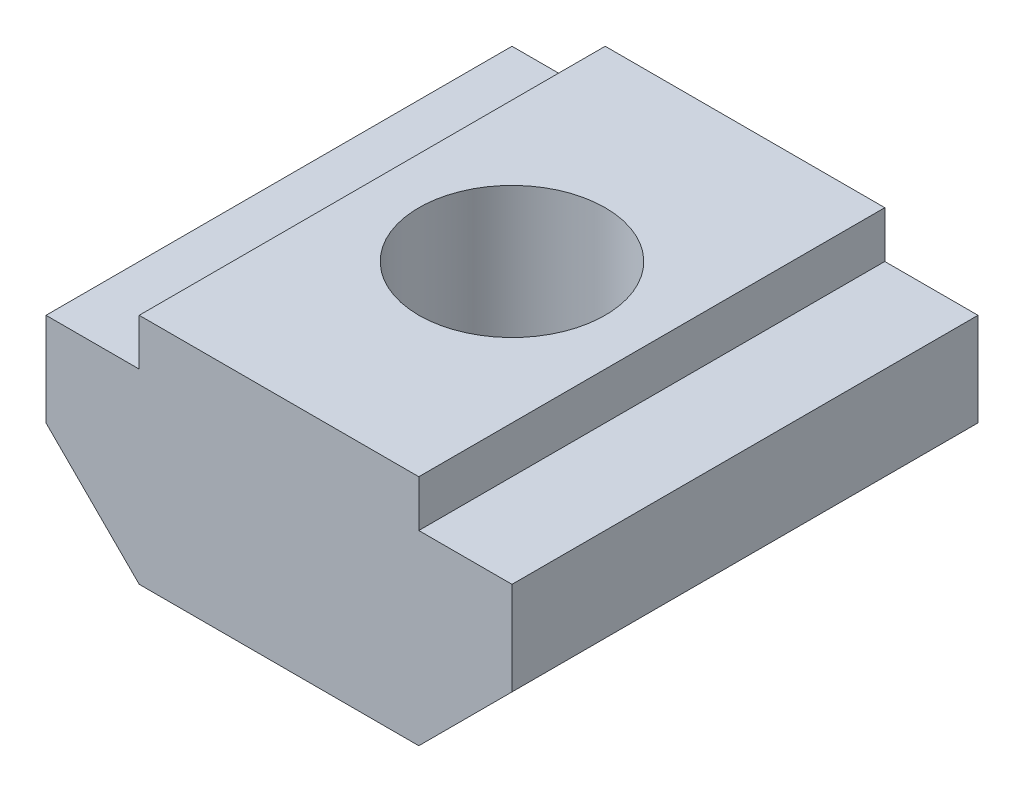
SolidWorks part; units mm, degrees
ref_plane "Plano frontal" through (0, 0, 0) normal (0, 0, 1) x (1, 0, 0)
ref_plane "Plano superior" through (0, 0, 0) normal (0, 1, 0) x (1, 0, 0)
ref_plane "Plano direito" through (0, 0, 0) normal (1, 0, 0) x (0, 0, -1)
sketch "Esboço1" plane through (0, 0, 0) normal (0, 0, 1) x (1, 0, 0)
  line L0 (-3, 0) -> (3, 0)
  line L1 (0, 0) -> (0, -1) construction
  line L2 (-5, -1) -> (-3, -1)
  line L3 (-3, 0) -> (-3, -1)
  line L4 (3, 0) -> (3, -1)
  line L5 (3, -1) -> (5, -1)
  line L6 (-5, -1) -> (-5, -5)
  line L7 (-5, -5) -> (5, -5)
  line L8 (5, -5) -> (5, -1)
  point P4 (0, 0)
  point P10 (0, -1)
  dimension "D1" = 6
  dimension "D2" = 10
  dimension "D3" = 1
  dimension "D4" = 4
extrude "Ressalto-extrusão1" add sketch "Esboço1" along normal blind 10
chamfer "Chanfro1" distance 2 angle 45 2 edges at (-5, -5, 5) (5, -5, 5)
sketch "Esboço2" plane through (0, 0, 0) normal (0, 1, 0) x (1, 0, 0)
  line L0 (0, 0) -> (0, -10) construction
  line L1 (3, -10) -> (-3, -10) construction
  circle A0 centre (0, -5) radius 2
  dimension "D1" = 4
extrude "Corte-extrusão1" cut sketch "Esboço2" against normal up to surface (5 mm away) up to face at (0, -5, 5)
ref_plane "Plano1" through (0, 0, 0) normal (-1, 0, 0) x (0, 0, 1)
